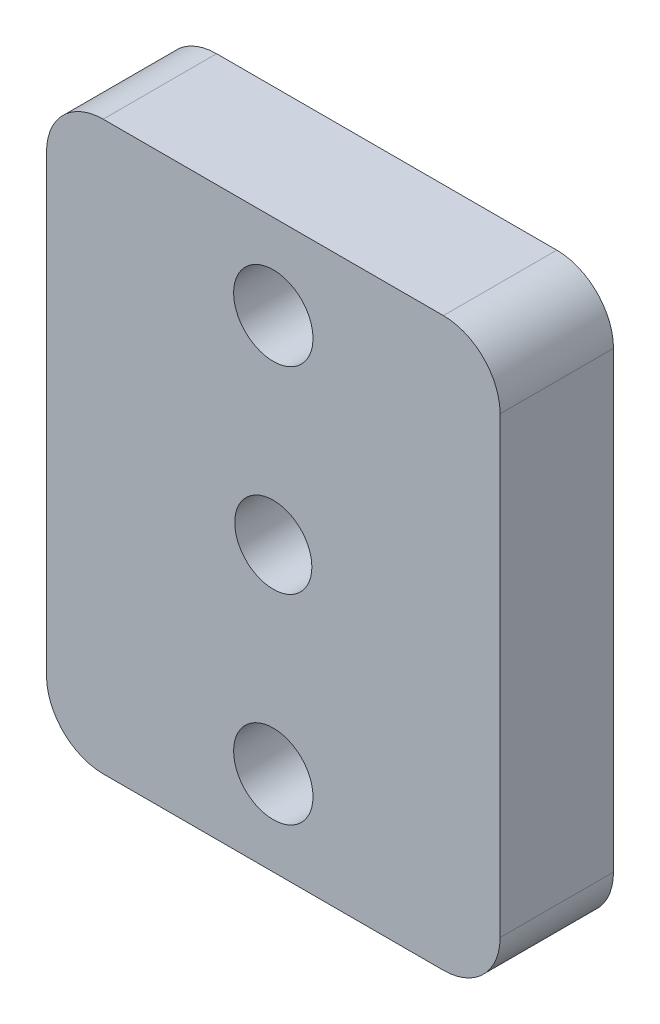
SolidWorks part; units mm, degrees
ref_plane "Front" through (0, 0, 0) normal (0, 0, 1) x (1, 0, 0)
ref_plane "Top" through (0, 0, 0) normal (0, 1, 0) x (1, 0, 0)
ref_plane "Right" through (0, 0, 0) normal (1, 0, 0) x (0, 0, -1)
sketch "Esquisse1" plane through (0, 0, 0) normal (0, 0, 1) x (1, 0, 0)
  line L1 (0, 0) -> (40, 0)
  line L2 (0, 0) -> (0, 50)
  line L3 (0, 50) -> (40, 50)
  line L4 (40, 0) -> (40, 50)
  dimension "D1" = 40
  dimension "D2" = 50
extrude "Boss.-Extru.1" add sketch "Esquisse1" along normal blind 10
sketch "Esquisse2" plane through (0, 0, 10) normal (0, 0, 1) x (1, 0, 0)
  line L0 (20, 0) -> (20, 50) construction
  line L1 (0, 0) -> (40, 0) construction
  line L2 (40, 50) -> (0, 50) construction
  line L3 (20, 25) -> (0, 25) construction
  line L4 (0, 50) -> (0, 0) construction
  circle A0 centre (20, 25) radius 3.4
  circle A1 centre (20, 7.5) radius 3.5
  circle A2 centre (20, 42.5) radius 3.5
  dimension "D1" = 6.8
  dimension "D2" = 7
  dimension "D3" = 35
extrude "Enlèv. mat.-Extru.1" cut sketch "Esquisse2" against normal through all both and the other way through all
fillet "Congé1" radius 5 4 edges at (0, 0, 5) (40, 0, 5) (40, 50, 5) (0, 50, 5)
